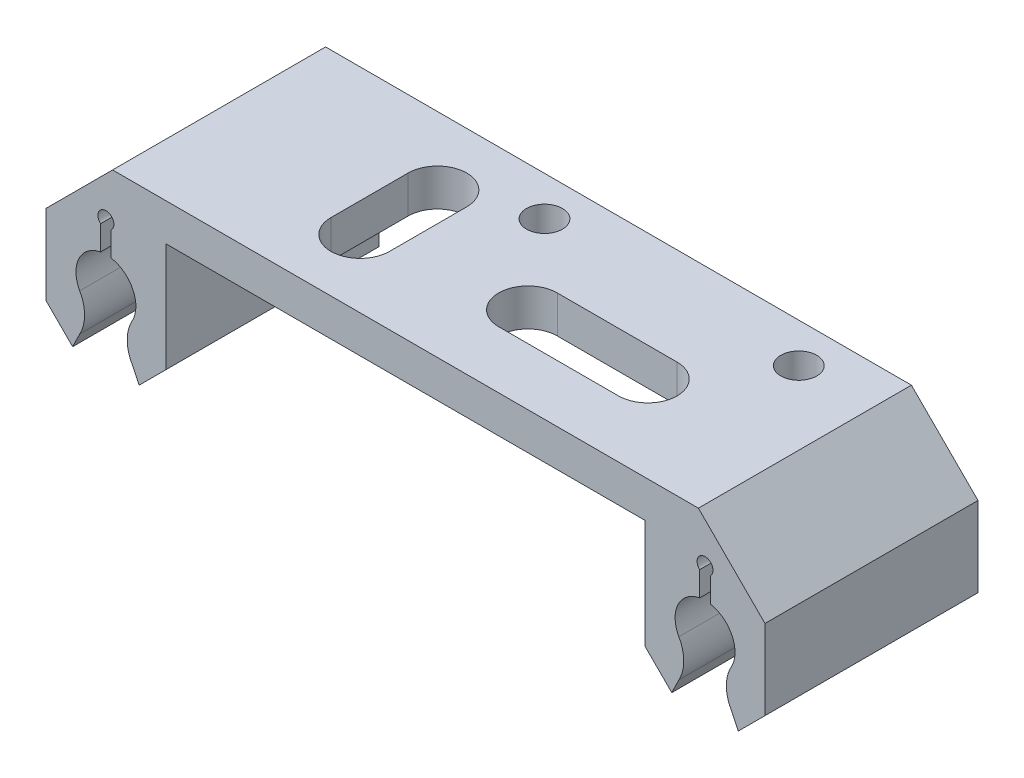
SolidWorks part; units mm, degrees
ref_plane "Front Plane" through (0, 0, 0) normal (0, 0, 1) x (1, 0, 0)
ref_plane "Top Plane" through (0, 0, 0) normal (0, 1, 0) x (1, 0, 0)
ref_plane "Right Plane" through (0, 0, 0) normal (1, 0, 0) x (0, 0, -1)
sketch "Sketch1" plane through (0, 0, 0) normal (0, 0, 1) x (1, 0, 0)
  line L0 (0, 0) -> (0, 13)
  line L1 (0, 13) -> (54, 13)
  line L2 (54, 13) -> (54, 0)
  line L3 (54, 0) -> (45, 0)
  line L4 (45, 0) -> (45, 10.2)
  line L5 (45, 10.2) -> (9, 10.2)
  line L6 (9, 10.2) -> (9, 0)
  line L7 (9, 0) -> (0, 0)
  point P4 (4.5, 0)
  dimension "D1" = 9
  dimension "D2" = 9
  dimension "D3" = 54
  dimension "D4" = 2.8
  dimension "D5" = 10.2
extrude "Boss-Extrude1" add sketch "Sketch1" along normal blind 16
chamfer "Chamfer1" distance 2 angle 45 4 edges at (54, 0, 8) (45, 0, 8) (0, 0, 8) (9, 0, 8)
sketch "Sketch2" plane through (0, 0, 16) normal (0, 0, 1) x (1, 0, 0)
  line L0 (2, 0) -> (7, 0) construction
  line L1 (47, 0) -> (52, 0) construction
  line L2 (9, 2) -> (9, 10.2) construction
  line L3 (45, 10.2) -> (45, 2) construction
  circle A0 centre (4.5, 5) radius 2.25
  circle A1 centre (49.5, 5) radius 2.25
  dimension "D5" = 4.5
  dimension "D6" = 4.5
  dimension "D1" = 5
  dimension "D2" = 5
  dimension "D3" = 4.5
  dimension "D4" = 4.5
extrude "Cut-Extrude1" cut sketch "Sketch2" against normal blind 16
sketch "Sketch3" plane through (0, 0, 16) normal (0, 0, 1) x (1, 0, 0)
  line L0 (2, 0) -> (7, 0) construction
  line L1 (4.1, 5) -> (4.1, 9.5) construction
  line L2 (4.1, 5) -> (4.9, 5) construction
  line L3 (4.1, 9.5) -> (4.9, 9.5) construction
  line L4 (4.9, 5) -> (4.9, 9.5) construction
  line L5 (4.1, 5) -> (4.9, 9.5) construction
  line L6 (4.1, 9.5) -> (4.9, 5) construction
  line L7 (2.5349, 3.9041) -> (6.4651, 3.9041)
  line L8 (2.5349, 1.0959) -> (2, 0)
  line L9 (2, 0) -> (7, 0)
  line L10 (7, 0) -> (6.4651, 1.0959)
  line L11 (2.9, 0) -> (2.9, 3.9041) construction
  line L12 (6.1, 3.9041) -> (6.1, 0) construction
  line L13 (4.1, 9.0528) -> (4.1, 6.7946)
  line L14 (4.1, 6.7946) -> (4.9, 6.7946)
  line L15 (4.9, 6.7946) -> (4.9, 9.0528)
  arc A0 (2.25, 0) -> (6.75, 0) centre (4.5, 0) cw construction
  circle A1 centre (4.5, 5) radius 2.25 construction
  arc A2 (2.5349, 3.9041) -> (2.5349, 1.0959) centre (0.0173, 2.5) cw
  arc A3 (6.4651, 3.9041) -> (6.4651, 1.0959) centre (8.9827, 2.5) ccw
  circle A4 centre (4.5, 9.5) radius 0.6 construction
  arc A5 (4.1, 9.0528) -> (4.9, 9.0528) centre (4.5, 9.5) cw
  point P6 (4.5, 7.25)
  dimension "D1" = 2.25
  dimension "D5" = 3.2
  dimension "D6" = 1.2
  dimension "D2" = 0.8
  dimension "D3" = 0.4
  dimension "D4" = 4.5
extrude "Cut-Extrude2" cut sketch "Sketch3" against normal blind 16
ref_plane "Plane1" through (27, 0, 0) normal (1, 0, 0) x (0, 0, -1)
mirror "Mirror1" about plane through (27, 0, 0) normal (1, 0, 0) of "Cut-Extrude2"
sketch "Sketch4" plane through (0, 13, 0) normal (0, 1, 0) x (1, 0, 0)
  line L0 (54, 0) -> (0, 0) construction
  line L1 (7.2, -16) -> (46.8, -16)
  line L2 (7.2, -16) -> (7.2, 0)
  line L3 (7.2, 0) -> (46.8, 0)
  line L4 (46.8, -16) -> (46.8, 0)
  line L5 (7.2, -16) -> (46.8, 0) construction
  line L6 (7.2, 0) -> (46.8, -16) construction
  line L7 (29.7, -9.5) -> (38.7, -9.5) construction
  line L8 (29.7, -7.3) -> (38.7, -7.3)
  line L9 (29.7, -11.7) -> (38.7, -11.7)
  line L10 (18.5, -5.1) -> (18.5, -10.9) construction
  line L11 (20.7, -5.1) -> (20.7, -10.9)
  line L12 (16.3, -5.1) -> (16.3, -10.9)
  circle A0 centre (43.5, -2.96) radius 1.6
  circle A1 centre (24.4, -2.96) radius 1.6
  arc A2 (29.7, -7.3) -> (29.7, -11.7) centre (29.7, -9.5) ccw
  arc A3 (38.7, -11.7) -> (38.7, -7.3) centre (38.7, -9.5) ccw
  arc A4 (20.7, -5.1) -> (16.3, -5.1) centre (18.5, -5.1) ccw
  arc A5 (16.3, -10.9) -> (20.7, -10.9) centre (18.5, -10.9) ccw
  point P0 (27, -8)
  point P8 (27, 0)
  point P12 (34.2, -9.5)
  point P21 (18.5, -8)
  point P27 (7.2, -8)
  dimension "D4" = 3.2
  dimension "D5" = 3.2
  dimension "D1" = 8
  dimension "D2" = 39.6
  dimension "D3" = 16
  dimension "D6" = 3.3
  dimension "D7" = 2.96
  dimension "D8" = 22.4
  dimension "D9" = 4.4
  dimension "D10" = 6.5
  dimension "D11" = 9
  dimension "D12" = 12.6
  dimension "D13" = 4.4
  dimension "D14" = 11.3
  dimension "D15" = 5.8
sketch "Sketch5" plane through (0, 13, 0) normal (0, 1, 0) x (1, 0, 0)
  line L0 (18.5, -5.1) -> (18.5, -10.9) construction
  line L1 (20.7, -5.1) -> (20.7, -10.9)
  line L2 (16.3, -5.1) -> (16.3, -10.9)
  line L3 (29.7, -9.5) -> (38.7, -9.5) construction
  line L4 (29.7, -7.3) -> (38.7, -7.3)
  line L5 (29.7, -11.7) -> (38.7, -11.7)
  arc A0 (20.7, -5.1) -> (16.3, -5.1) centre (18.5, -5.1) ccw
  arc A1 (16.3, -10.9) -> (20.7, -10.9) centre (18.5, -10.9) ccw
  arc A2 (29.7, -7.3) -> (29.7, -11.7) centre (29.7, -9.5) ccw
  arc A3 (38.7, -11.7) -> (38.7, -7.3) centre (38.7, -9.5) ccw
  circle A4 centre (24.4, -2.96) radius 1.35
  circle A5 centre (43.5, -2.96) radius 1.35
  point P4 (18.5, -8)
  point P9 (34.2, -9.5)
  point P24 (34.2, -11.7)
  dimension "D3" = 2.7
  dimension "D4" = 2.7
  dimension "D1" = 4.4
  dimension "D2" = 4.4
extrude "Cut-Extrude3" cut sketch "Sketch5" against normal blind 16
chamfer "Chamfer3" distance 5 angle 45 2 edges at (54, 13, 8) (0, 13, 8)
